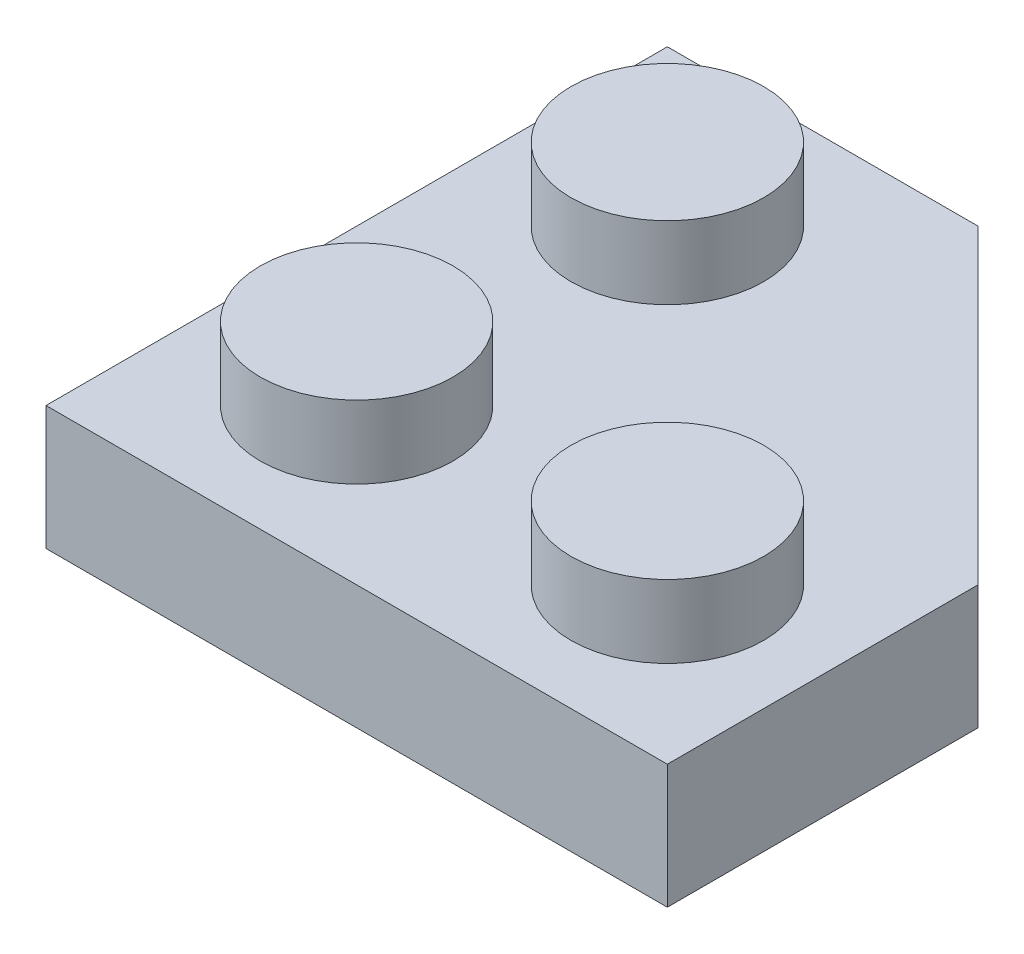
SolidWorks part; units mm, degrees
ref_plane "Front Plane" through (0, 0, 0) normal (0, 0, 1) x (1, 0, 0)
ref_plane "Top Plane" through (0, 0, 0) normal (0, 1, 0) x (1, 0, 0)
ref_plane "Right Plane" through (0, 0, 0) normal (1, 0, 0) x (0, 0, -1)
sketch "Sketch1" plane through (0, 0, 0) normal (0, 1, 0) x (1, 0, 0)
  line L1 (-7.9, 7.9) -> (7.9, 7.9)
  line L2 (-7.9, 7.9) -> (-7.9, -7.9)
  line L3 (-7.9, -7.9) -> (7.9, -7.9)
  line L4 (7.9, 7.9) -> (7.9, -7.9)
  line L5 (-7.9, 7.9) -> (7.9, -7.9) construction
  line L6 (-7.9, -7.9) -> (7.9, 7.9) construction
  point P0 (0, 0)
  dimension "D1" = 15.8
  dimension "D2" = 15.8
extrude "Boss-Extrude1" add sketch "Sketch1" against normal blind 3.15
sketch "Sketch2" plane through (0, 0, 0) normal (0, 1, 0) x (1, 0, 0)
  line L0 (-7.9, 7.9) -> (-7.9, -7.9) construction
  line L1 (7.9, 7.9) -> (-7.9, 7.9) construction
  line L2 (-7.9, -7.9) -> (7.9, -7.9) construction
  line L3 (7.9, -7.9) -> (7.9, 7.9) construction
  circle A0 centre (-3.95, 3.95) radius 2.45
  circle A1 centre (-3.95, -3.95) radius 2.45
  circle A2 centre (3.95, -3.95) radius 2.45
  dimension "D3" = 4.9
  dimension "D6" = 4.9
  dimension "D7" = 3.95
  dimension "D9" = 4.9
  dimension "D1" = 3.95
  dimension "D2" = 3.95
  dimension "D4" = 3.95
  dimension "D5" = 3.95
  dimension "D8" = 3.95
extrude "Boss-Extrude2" add sketch "Sketch2" along normal blind 1.85
sketch "Sketch3" plane through (0, 0, 0) normal (0, 1, 0) x (1, 0, 0)
  line L0 (0, 7.9) -> (7.9, 0)
  line L1 (7.9, 7.9) -> (-7.9, 7.9) construction
  line L2 (7.9, -7.9) -> (7.9, 7.9) construction
  line L5 (0, 7.9) -> (7.9, 7.9)
  line L6 (7.9, 7.9) -> (7.9, 0)
extrude "Cut-Extrude1" cut sketch "Sketch3" against normal through all and the other way through all
shell "Shell1" thickness 1.5
sketch "Sketch4" plane through (3.95, 0, -3.95) normal (0.7071, 0, -0.7071) x (-0.7071, 0, -0.7071)
  line L0 (-2.5, -1.5) -> (2.5, -1.5)
  line L1 (-2.5, -1.5) -> (-2.5, -3.15)
  line L2 (5.5861, -3.15) -> (-5.5861, -3.15) construction
  line L3 (2.5, -1.5) -> (2.5, -3.15)
  line L4 (2.5, -3.15) -> (-2.5, -3.15)
  line L5 (5.5861, 0) -> (-5.5861, 0) construction
  point P2 (0, -1.5)
  dimension "D1" = 5
  dimension "D2" = 1.5
extrude "Cut-Extrude2" cut sketch "Sketch4" against normal blind 1.5
fillet "Fillet1" radius 0.2 4 edges at (1.6519, -3.15, -5.1874) (1.6519, -1.5, -5.1874) (5.1874, -3.15, -1.6519) (5.1874, -1.5, -1.6519)
sketch "Sketch5" plane through (0, -1.5, 0) normal (0, -1, 0) x (1, 0, 0)
  circle A0 centre (0, 0) radius 3.25
  circle A1 centre (0, 0) radius 2.44
  dimension "D1" = 6.5
  dimension "D2" = 4.88
extrude "Boss-Extrude3" add sketch "Sketch5" along normal offset from surface (1.45 mm away) 0.2 up to face at (0.9327, -3.15, -0.9327)
